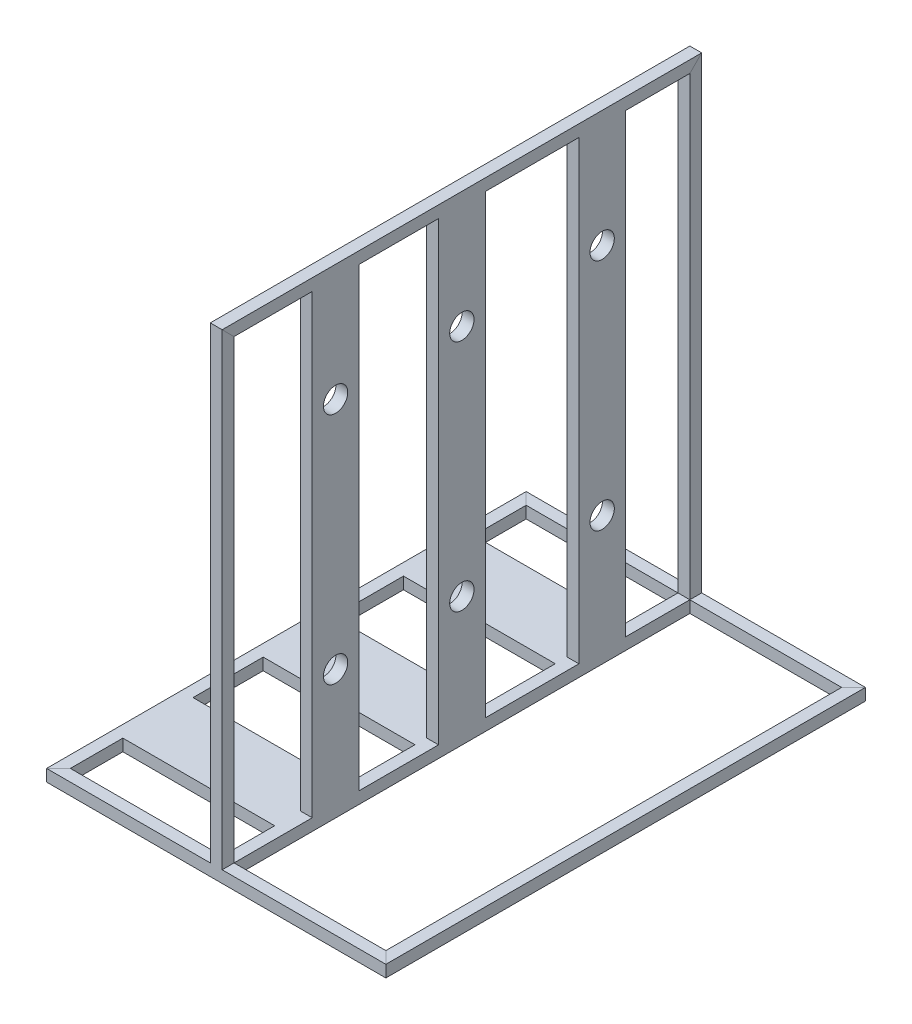
SolidWorks part; units mm, degrees
other "Markup1"
sketch "Sketch9" plane through (362.7, 1012.7, -512.7) normal (0.7948, 0.072, -0.6026) x (-0.6066, 0.1223, -0.7855)
other "Markup3"
sketch "Sketch11" plane through (-362.7, 1012.7, -512.7) normal (-0.9375, 0.3398, -0.075) x (-0.076, 0.0104, 0.9971)
other "Markup4"
sketch "Sketch12" plane through (-362.7, -12.7, -512.7) normal (-1, 0, 0) x (0, 0, 1)
other "Markup5"
sketch "Sketch13" plane through (-362.7, 1012.7, -512.7) normal (-0.9252, 0.0583, -0.375) x (-0.3754, 0.0037, 0.9269)
ref_plane "Front Plane" through (0, 0, 0) normal (0, 0, 1) x (1, 0, 0)
ref_plane "Top Plane" through (0, 0, 0) normal (0, 1, 0) x (1, 0, 0)
ref_plane "Right Plane" through (0, 0, 0) normal (1, 0, 0) x (0, 0, -1)
sketch "Sketch1" plane through (0, 0, 0) normal (0, 1, 0) x (1, 0, 0)
  line L1 (-350, -500) -> (350, -500)
  line L2 (-350, -500) -> (-350, 500)
  line L3 (-350, 500) -> (350, 500)
  line L4 (350, -500) -> (350, 500)
  line L5 (-350, -500) -> (350, 500) construction
  line L6 (-350, 500) -> (350, -500) construction
  point P0 (0, 0)
  dimension "D1" = 1000
  dimension "D2" = 700
sketch "Sketch2" plane through (0, 0, 0) normal (1, 0, 0) x (0, 0, -1)
  line L1 (512.7, -12.7) -> (487.3, -12.7)
  line L2 (512.7, -12.7) -> (512.7, 12.7)
  line L3 (512.7, 12.7) -> (487.3, 12.7)
  line L4 (487.3, -12.7) -> (487.3, 12.7)
  line L5 (512.7, -12.7) -> (487.3, 12.7) construction
  point P0 (500, 0)
  dimension "D1" = 25.4
  dimension "D2" = 25.4
sketch "Sketch4" plane through (0, 0, 0) normal (1, 0, 0) x (0, 0, -1)
  line L0 (-500, 0) -> (-500, 1000)
  line L1 (-500, 1000) -> (500, 1000)
  line L2 (500, 1000) -> (500, 0)
  line L3 (-500, 0) -> (500, 0)
  dimension "D1" = 1000
sweep "Sweep4" add profiles "Sketch2" path "Sketch1"
sketch "Sketch6" plane through (0, 12.7, 0) normal (0, 1, 0) x (1, 0, 0)
  line L0 (0, -500) -> (0, 500) construction
  line L1 (-12.7, 487.3) -> (12.7, 487.3)
  line L2 (-12.7, 487.3) -> (-12.7, 512.7)
  line L3 (-12.7, 512.7) -> (12.7, 512.7)
  line L4 (12.7, 487.3) -> (12.7, 512.7)
  line L5 (-12.7, 487.3) -> (12.7, 512.7) construction
  line L6 (-12.7, 512.7) -> (12.7, 487.3) construction
  line L7 (0, 512.7) -> (362.7, 512.7) construction
  point P0 (0, 500)
  dimension "D1" = 25.4
  dimension "D2" = 25.4
sweep "Sweep5" add profiles "Sketch6" path "Sketch4"
sketch "Sketch7" plane through (0, 12.7, 0) normal (0, 1, 0) x (1, 0, 0)
  line L3 (12.7, -512.7) -> (12.7, 512.7) construction
  line L4 (-12.7, -50) -> (12.7, -50)
  line L5 (-12.7, -50) -> (-12.7, 50)
  line L6 (-12.7, 50) -> (12.7, 50)
  line L7 (12.7, -50) -> (12.7, 50)
  line L8 (-12.7, -50) -> (12.7, 50) construction
  line L9 (-12.7, 50) -> (12.7, -50) construction
  line L10 (-12.7, 0) -> (12.7, 0) construction
  line L11 (-12.7, -512.7) -> (-12.7, 512.7) construction
  line L13 (-12.7, -50) -> (-12.7, 50)
  line L14 (-12.7, -50) -> (12.7, -50)
  line L15 (12.7, -50) -> (12.7, 50)
  line L16 (-12.7, 50) -> (12.7, 50)
  line L21 (-12.7, 350) -> (-12.7, 450) [skipped]
  line L22 (-12.7, 350) -> (12.7, 350) [skipped]
  line L23 (12.7, 350) -> (12.7, 450) [skipped]
  line L24 (-12.7, 450) -> (12.7, 450) [skipped]
  line L25 (-12.7, -450) -> (-12.7, -350) [skipped]
  line L26 (-12.7, -450) -> (12.7, -450) [skipped]
  line L27 (12.7, -450) -> (12.7, -350) [skipped]
  line L28 (-12.7, -350) -> (12.7, -350) [skipped]
  line L29 (-12.7, -320.1768) -> (-12.7, -220.1768)
  line L30 (-12.7, -320.1768) -> (12.7, -320.1768)
  line L31 (12.7, -320.1768) -> (12.7, -220.1768)
  line L32 (-12.7, -220.1768) -> (12.7, -220.1768)
  line L33 (-12.7, -320.1768) -> (12.7, -220.1768) construction
  line L34 (-12.7, -220.1768) -> (12.7, -320.1768) construction
  line L35 (-12.7, -300) -> (12.7, -300) construction
  line L36 (-12.7, -25) -> (-12.7, 25)
  line L38 (12.7, -25) -> (12.7, 25)
  line L42 (-12.7, 0) -> (12.7, 0) construction
  line L43 (-12.7, 350) -> (12.7, 250) construction
  line L44 (-12.7, 350) -> (12.7, 350)
  line L45 (-12.7, 250) -> (-12.7, 350)
  line L46 (-12.7, 250) -> (12.7, 250)
  line L47 (12.7, 250) -> (12.7, 350)
  point P0 (0, 0)
  point P1 (0, 0)
  point P3 (0, 0)
  point P6 (0, 0)
  point P51 (0, 0)
  line M7 (-12.7, 487.3) -> (-12.7, -487.3)
  line M9 (12.7, -487.3) -> (12.7, 487.3)
  dimension "D1" = 100
  dimension "D2" = 2
  dimension "D3" = 2
  dimension "D4" = 2
  dimension "D5" = 100
  dimension "D6" = 100
extrude "Boss-Extrude1" add sketch "Sketch7" along normal blind 974.6 contours L6 L4 M7 M9 | L32 L30 M7 M9 | L46 L44 M7 M9
sketch "Sketch8" plane through (-12.7, 0, 0) normal (-1, 0, 0) x (0, 0, 1)
  line L0 (-375, -12.7) -> (-375, 12.7)
  line L1 (-75, -12.7) -> (75, -12.7)
  line L2 (-75, -12.7) -> (-75, 12.7)
  line L3 (-75, 12.7) -> (75, 12.7)
  line L4 (75, -12.7) -> (75, 12.7)
  line L5 (-75, -12.7) -> (75, 12.7) construction
  line L6 (-75, 12.7) -> (75, -12.7) construction
  line L7 (-375, -12.7) -> (-225, -12.7)
  line L8 (-225, -12.7) -> (-225, 12.7)
  line L9 (-375, 12.7) -> (-225, 12.7)
  line L10 (225, -12.7) -> (225, 12.7)
  line L11 (225, 12.7) -> (375, -12.7) construction
  line L12 (225, -12.7) -> (375, 12.7) construction
  line L13 (225, 12.7) -> (375, 12.7)
  line L14 (375, -12.7) -> (375, 12.7)
  line L15 (225, -12.7) -> (375, -12.7)
  point P0 (0, 0)
  dimension "D1" = 25.4
  dimension "D2" = 150
  dimension "D3" = 2
  dimension "D4" = 2
extrude "Boss-Extrude2" add sketch "Sketch8" along normal up to surface (324.6 mm away) up to face at (-337.3, 0, 0)
sketch "Sketch14" plane through (12.7, 0, 0) normal (1, 0, 0) x (0, 0, -1)
  line L0 (-320.1768, 762.7) -> (-220.1768, 762.7) construction
  line L1 (-320.1768, 987.3) -> (-320.1768, 12.7) construction
  line L2 (-220.1768, 987.3) -> (-220.1768, 12.7) construction
  line L3 (-220.1768, 762.7) -> (-220.1768, 12.7) construction
  line L4 (-50.1768, 762.7) -> (49.8232, 762.7) construction
  line L5 (49.8232, 762.7) -> (50, 12.7) construction
  line L6 (249.8232, 762.7) -> (349.8232, 762.7) construction
  line L7 (-320.1768, 262.7) -> (-220.1768, 262.7) construction
  line L8 (-50.1768, 262.7) -> (49.8232, 262.7) construction
  line L9 (249.8232, 262.7) -> (349.8232, 262.7) construction
  circle A0 centre (-270.1768, 762.7) radius 26
  circle A1 centre (-0.1768, 762.7) radius 26
  circle A2 centre (299.8232, 762.7) radius 26
  circle A3 centre (-270.1768, 262.7) radius 26
  circle A4 centre (-0.1768, 262.7) radius 26
  circle A5 centre (299.8232, 262.7) radius 26
  point P11 (-270.1768, 762.7)
  dimension "D1" = 52
  dimension "D4" = 2
  dimension "D2" = 750
  dimension "D3" = 2
  dimension "D5" = 2
extrude "Cut-Extrude1" cut sketch "Sketch14" along a picked direction on the side against the normal blind 1115
